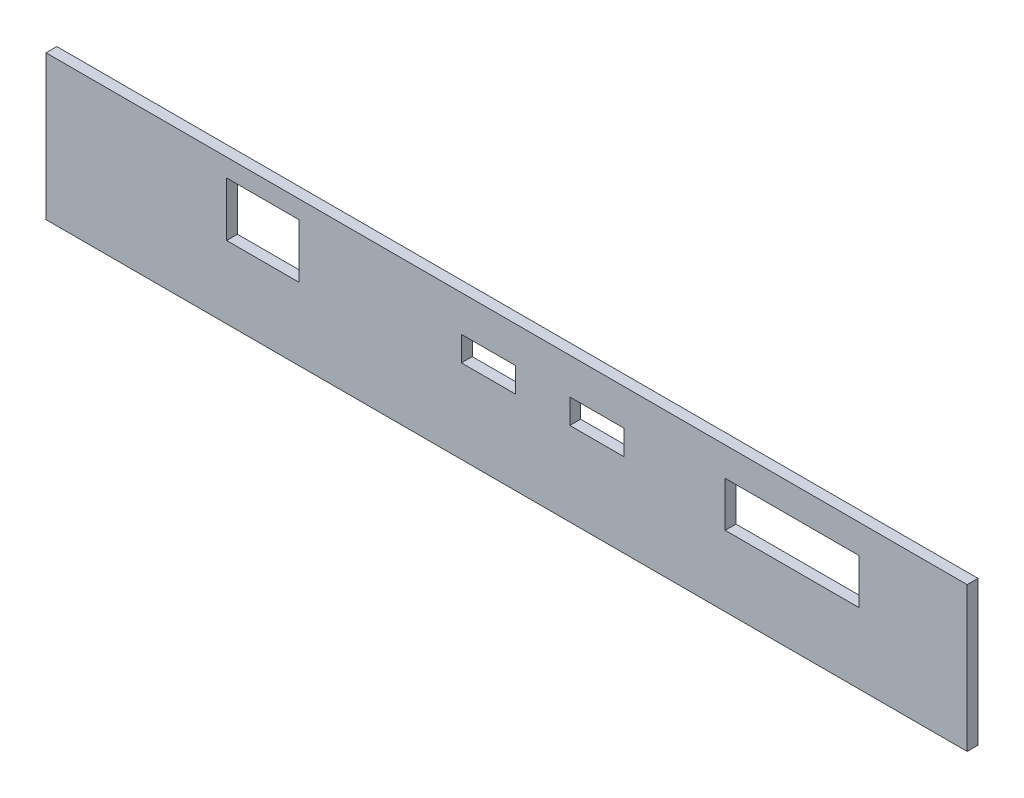
SolidWorks part; units mm, degrees
ref_plane "Front Plane" through (0, 0, 0) normal (0, 0, 1) x (1, 0, 0)
ref_plane "Top Plane" through (0, 0, 0) normal (0, 1, 0) x (1, 0, 0)
ref_plane "Right Plane" through (0, 0, 0) normal (1, 0, 0) x (0, 0, -1)
sketch "Sketch1" plane through (0, 0, 0) normal (0, 0, 1) x (1, 0, 0)
  line L1 (-122.2716, 14.6468) -> (132.7284, 14.6468)
  line L2 (-122.2716, 14.6468) -> (-122.2716, -25.3532)
  line L3 (-122.2716, -25.3532) -> (132.7284, -25.3532)
  line L4 (132.7284, 14.6468) -> (132.7284, -25.3532)
  line L5 (102.7284, 14.6468) -> (65.7284, 14.6468)
  line L6 (102.7284, 6.6468) -> (102.7284, -5.8325)
  line L7 (102.7284, -5.8325) -> (65.7284, -5.8325)
  line L8 (65.7284, 6.6468) -> (65.7284, -5.8325)
  line L9 (37.7284, 14.6468) -> (22.7284, 14.6468)
  line L10 (37.7284, 4.6468) -> (37.7284, -2.1913)
  line L11 (37.7284, -2.1913) -> (22.7284, -2.1913)
  line L12 (22.7284, 4.6468) -> (22.7284, -2.1913)
  line L13 (-7.2716, 14.6468) -> (7.7284, 14.6468)
  line L14 (-7.2716, 4.6468) -> (-7.2716, -2.1913)
  line L15 (-7.2716, -2.1913) -> (7.7284, -2.1913)
  line L16 (7.7284, 4.6468) -> (7.7284, -2.1913)
  line L17 (-72.2716, 14.6468) -> (-52.2716, 14.6468)
  line L18 (-72.2716, 9.6468) -> (-72.2716, -5.3532)
  line L19 (-72.2716, -5.3532) -> (-52.2716, -5.3532)
  line L20 (-52.2716, 9.6468) -> (-52.2716, -5.3532)
  line L21 (65.7284, 6.6468) -> (102.7284, 6.6468)
  line L22 (22.7284, 4.6468) -> (37.7284, 4.6468)
  line L23 (-7.2716, 4.6468) -> (7.7284, 4.6468)
  line L24 (-72.2716, 9.6468) -> (-52.2716, 9.6468)
  dimension "D1" = 40
  dimension "D2" = 255
  dimension "D3" = 30
  dimension "D4" = 67
  dimension "D5" = 95
  dimension "D6" = 110
  dimension "D7" = 125
  dimension "D8" = 140
  dimension "D9" = 185
  dimension "D10" = 205
  dimension "D12" = 32
  dimension "D13" = 30
  dimension "D14" = 35
  dimension "D15" = 20
extrude "Boss-Extrude1" add sketch "Sketch1" along normal blind 3 contours L4 L1 L2 L3 L8 L21 L6 L7 L12 L22 L10 L11 L14 L23 L16 L15 L18 L24 L20 L19
